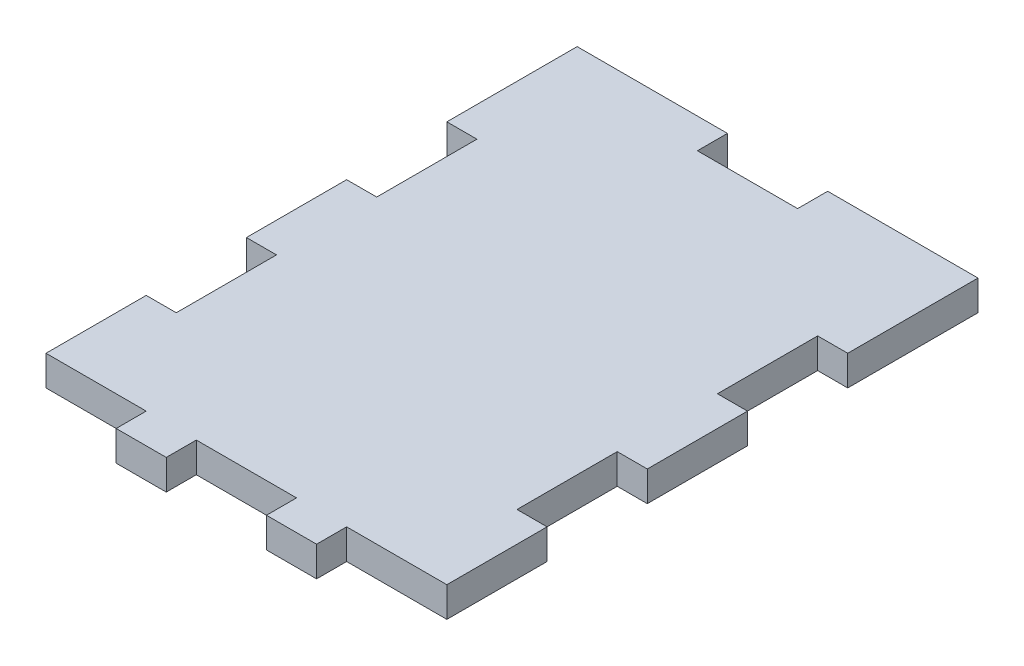
SolidWorks part; units mm, degrees
ref_plane "Plano frontal" through (0, 0, 0) normal (0, 0, 1) x (1, 0, 0)
ref_plane "Plano superior" through (0, 0, 0) normal (0, 1, 0) x (1, 0, 0)
ref_plane "Plano direito" through (0, 0, 0) normal (1, 0, 0) x (0, 0, -1)
sketch "Esboço1" plane through (0, 0, 0) normal (0, 1, 0) x (1, 0, 0)
  line L0 (-80, 80) -> (-74, 80)
  line L1 (0, 0) -> (-20, 0)
  line L2 (0, 0) -> (0, 20)
  line L3 (0, 106) -> (-30, 106)
  line L4 (-80, 0) -> (-80, 20)
  line L5 (-74, 80) -> (-74, 60)
  line L6 (-74, 60) -> (-80, 60)
  line L7 (-80, 60) -> (-80, 40)
  line L8 (-80, 40) -> (-74, 40)
  line L9 (-74, 40) -> (-74, 20)
  line L10 (-74, 20) -> (-80, 20)
  line L11 (-60, 0) -> (-60, -6)
  line L12 (-60, -6) -> (-50, -6)
  line L13 (-50, -6) -> (-50, 0)
  line L14 (-50, 0) -> (-30, 0)
  line L15 (-30, 0) -> (-30, -6)
  line L16 (-30, -6) -> (-20, -6)
  line L17 (-20, -6) -> (-20, 0)
  line L18 (0, 20) -> (-6, 20)
  line L19 (-6, 20) -> (-6, 40)
  line L20 (-6, 40) -> (0, 40)
  line L21 (0, 60) -> (-6, 60)
  line L22 (-6, 60) -> (-6, 80)
  line L23 (-6, 80) -> (0, 80)
  line L27 (-50, 106) -> (-50, 100)
  line L28 (-50, 100) -> (-30, 100)
  line L29 (-30, 100) -> (-30, 106)
  line L30 (-50, 106) -> (-80, 106)
  line L31 (-80, 80) -> (-80, 106)
  line L33 (-60, 0) -> (-80, 0)
  line L35 (0, 40) -> (0, 60)
  line L36 (0, 80) -> (0, 106)
  dimension "D1" = 80
  dimension "D2" = 106
  dimension "D3" = 20
  dimension "D4" = 10
  dimension "D5" = 6
  dimension "D6" = 20
  dimension "D7" = 6
  dimension "D8" = 20
extrude "Ressalto-extrusão1" add sketch "Esboço1" along normal blind 6
